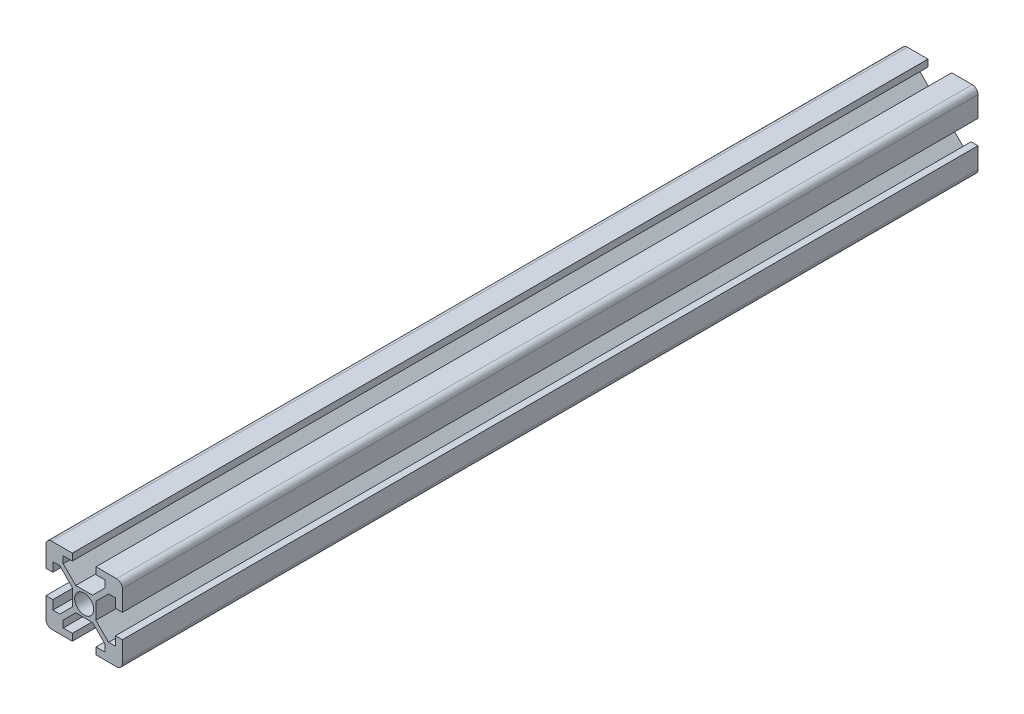
SolidWorks part; units mm, degrees
ref_plane "前视基准面" through (0, 0, 0) normal (0, 0, 1) x (1, 0, 0)
ref_plane "上视基准面" through (0, 0, 0) normal (0, 1, 0) x (1, 0, 0)
ref_plane "右视基准面" through (0, 0, 0) normal (1, 0, 0) x (0, 0, -1)
sketch "草图1" plane through (0, 0, 0) normal (0, 0, 1) x (1, 0, 0)
  line L0 (-10, -3.1) -> (-8.2, -3.1)
  line L1 (-8.5, 10) -> (8.5, 10)
  line L2 (-10, 8.5) -> (-10, -8.5)
  line L3 (-8.5, -10) -> (8.5, -10)
  line L4 (10, 8.5) -> (10, -8.5)
  line L5 (-10, 10) -> (10, -10) construction
  line L6 (-10, -10) -> (10, 10) construction
  line L7 (-3.0541, 3.1) -> (3.0541, 3.1)
  line L8 (-3.0541, 3.1) -> (-3.0541, -3.1)
  line L9 (-3.0541, -3.1) -> (3.0541, -3.1)
  line L10 (3.0541, 3.1) -> (3.0541, -3.1)
  line L11 (-3.0541, 3.1) -> (3.0541, -3.1) construction
  line L12 (-3.0541, -3.1) -> (3.0541, 3.1) construction
  line L13 (-8.2, -3.1) -> (-8.2, -5.5)
  line L14 (-8.2, -5.5) -> (-6.3971, -5.5)
  line L15 (-6.3971, -5.5) -> (-3.0541, -2.1571)
  line L16 (-5.5, 6.3971) -> (-2.1571, 3.0541)
  line L17 (-5.5, 8.2) -> (-5.5, 6.3971)
  line L18 (-3.1, 8.2) -> (-5.5, 8.2)
  line L19 (-3.1, 10) -> (-3.1, 8.2)
  line L20 (6.3971, 5.5) -> (3.0541, 2.1571)
  line L21 (8.2, 5.5) -> (6.3971, 5.5)
  line L22 (8.2, 3.1) -> (8.2, 5.5)
  line L23 (10, 3.1) -> (8.2, 3.1)
  line L24 (5.5, -6.3971) -> (2.1571, -3.0541)
  line L25 (5.5, -8.2) -> (5.5, -6.3971)
  line L26 (3.1, -8.2) -> (5.5, -8.2)
  line L27 (3.1, -10) -> (3.1, -8.2)
  line L28 (-3.1, -10) -> (-3.1, -8.2)
  line L29 (-3.1, -8.2) -> (-5.5, -8.2)
  line L30 (-5.5, -8.2) -> (-5.5, -6.3971)
  line L31 (-5.5, -6.3971) -> (-2.1571, -3.0541)
  line L32 (-8.2, 5.5) -> (-6.3971, 5.5)
  line L33 (-6.3971, 5.5) -> (-3.0541, 2.1571)
  line L34 (-8.2, 3.1) -> (-8.2, 5.5)
  line L35 (-10, 3.1) -> (-8.2, 3.1)
  line L36 (5.5, 8.2) -> (5.5, 6.3971)
  line L37 (5.5, 6.3971) -> (2.1571, 3.0541)
  line L38 (3.1, 8.2) -> (5.5, 8.2)
  line L39 (3.1, 10) -> (3.1, 8.2)
  line L40 (8.2, -5.5) -> (6.3971, -5.5)
  line L41 (6.3971, -5.5) -> (3.0541, -2.1571)
  line L42 (8.2, -3.1) -> (8.2, -5.5)
  line L43 (10, -3.1) -> (8.2, -3.1)
  circle A0 centre (0, 0) radius 2.5
  arc A1 (-10, 8.5) -> (-8.5, 10) centre (-8.5, 8.5) cw
  arc A2 (-10, -8.5) -> (-8.5, -10) centre (-8.5, -8.5) ccw
  arc A3 (8.5, 10) -> (10, 8.5) centre (8.5, 8.5) cw
  arc A4 (10, -8.5) -> (8.5, -10) centre (8.5, -8.5) cw
  point P0 (0, 0)
  point P20 (0, 0)
  point P26 (0, 0)
  point P32 (0, 0)
  point P38 (0, 0)
  point P60 (0, 0)
  dimension "D1" = 4
  dimension "D3" = 1.5
  dimension "D4" = 1.5
  dimension "D5" = 1.5
  dimension "D2" = 4
extrude "凸台-拉伸1" add sketch "草图1" along normal blind 950
sketch "草图2" plane through (0, 0, 950) normal (0, 0, 1) x (1, 0, 0)
  line L1 (82.4853, -16.9043) -> (-27.463, -16.9043)
  line L2 (82.4853, -16.9043) -> (82.4853, 12.5397)
  line L3 (82.4853, 12.5397) -> (-27.463, 12.5397)
  line L4 (-27.463, -16.9043) -> (-27.463, 12.5397)
  line L5 (82.4853, -16.9043) -> (-27.463, 12.5397) construction
  line L6 (82.4853, 12.5397) -> (-27.463, -16.9043) construction
  point P0 (27.5111, -2.1823)
extrude "切除-拉伸1" cut sketch "草图2" against normal blind 725.86
sketch "草图5" plane through (0, 0, 0) normal (0, 0, -1) x (-1, 0, 0)
  line L1 (84.8915, -120.2256) -> (-14.487, -120.2256)
  line L2 (84.8915, -120.2256) -> (84.8915, 31.2339)
  line L3 (84.8915, 31.2339) -> (-14.487, 31.2339)
  line L4 (-14.487, -120.2256) -> (-14.487, 31.2339)
  line L5 (84.8915, -120.2256) -> (-14.487, 31.2339) construction
  line L6 (84.8915, 31.2339) -> (-14.487, -120.2256) construction
  point P0 (35.2022, -44.4958)
